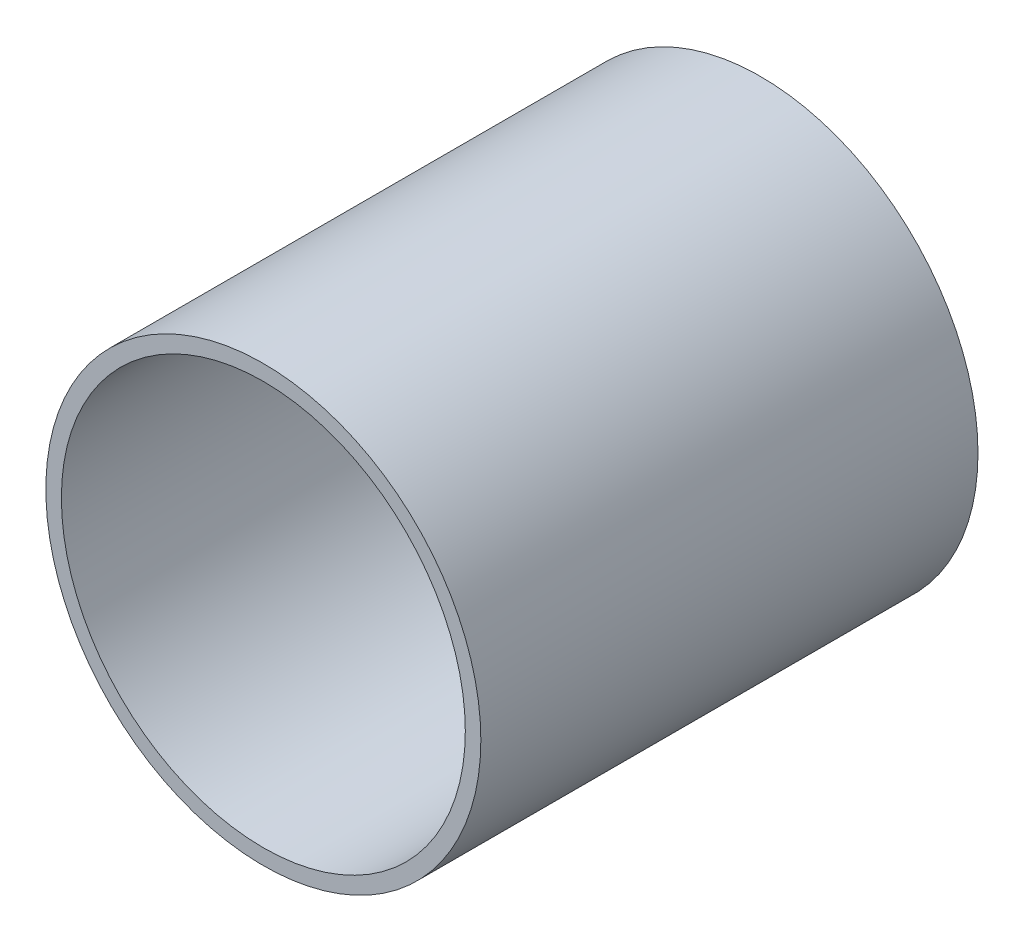
SolidWorks part; units mm, degrees
ref_plane "Front Plane" through (0, 0, 0) normal (0, 0, 1) x (1, 0, 0)
ref_plane "Top Plane" through (0, 0, 0) normal (0, 1, 0) x (1, 0, 0)
ref_plane "Right Plane" through (0, 0, 0) normal (1, 0, 0) x (0, 0, -1)
sketch "Sketch1" plane through (0, 0, 0) normal (0, 0, 1) x (1, 0, 0)
  circle A0 centre (0, 0) radius 88.9
  circle A1 centre (0, 0) radius 82.55
  dimension "D1" = 165.1
  dimension "D2" = 6.35
extrude "Boss-Extrude1" add sketch "Sketch1" along normal blind 203.2
